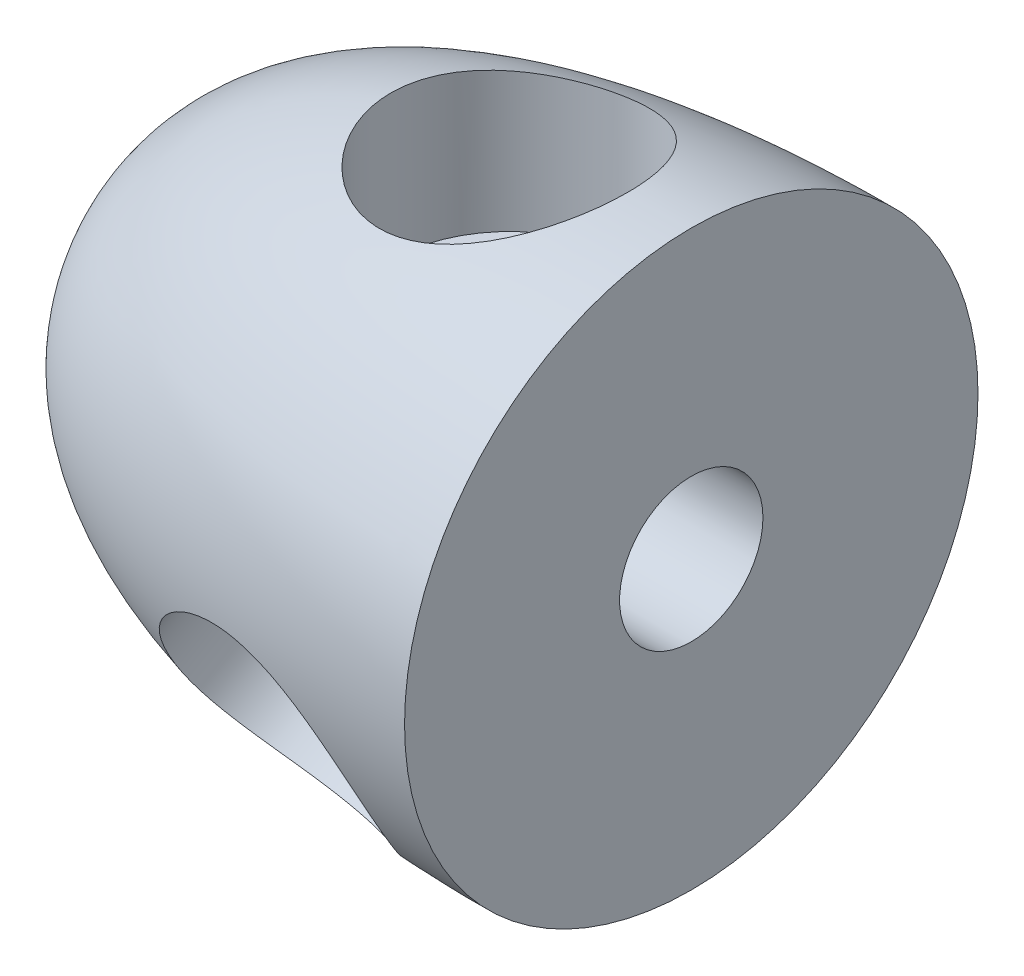
SolidWorks part; units mm, degrees
ref_plane "Front Plane" through (0, 0, 0) normal (0, 0, 1) x (1, 0, 0)
ref_plane "Top Plane" through (0, 0, 0) normal (0, 1, 0) x (1, 0, 0)
ref_plane "Right Plane" through (0, 0, 0) normal (1, 0, 0) x (0, 0, -1)
sketch "Sketch1" plane through (0, 0, 0) normal (0, 0, 1) x (1, 0, 0)
  line L0 (0, 20) -> (0, 0)
  line L1 (0, 0) -> (-38.5, 0)
  line L3 (17.354, 20) -> (-17.354, 20) construction
  line L4 (-38.5, 13.9331) -> (-38.5, -13.9331) construction
  spline S0 degree 3 poles (-38.5, 0) (-38.5, 17.4164) (-14.4616, 20) (0, 20) knots 0 0 0 0 1 1 1 1
  dimension "D1" = 38.5
  dimension "D2" = 20
revolve "Revolve1" add sketch "Sketch1" angle 360 about L1
sketch "Sketch2" plane through (0, 0, 0) normal (1, 0, 0) x (0, 0, -1)
  circle A0 centre (0, 0) radius 5
  dimension "D1" = 10
extrude "Cut-Extrude1" cut sketch "Sketch2" against normal blind 12.7
ref_plane "Plane1" through (0, 7.6, 0) normal (0, 1, 0) x (1, 0, 0)
sketch "Sketch3" plane through (0, 7.6, 0) normal (0, 1, 0) x (1, 0, 0)
  circle A0 centre (-12.7, 0) radius 8.25
  dimension "D1" = 16.5
  dimension "D2" = 12.7
extrude "Cut-Extrude2" cut sketch "Sketch3" along normal through all
pattern_circular "CirPattern1" count 3 over 360 about axis through (0, 0, 0) along (1, 0, 0) of "Cut-Extrude2"
